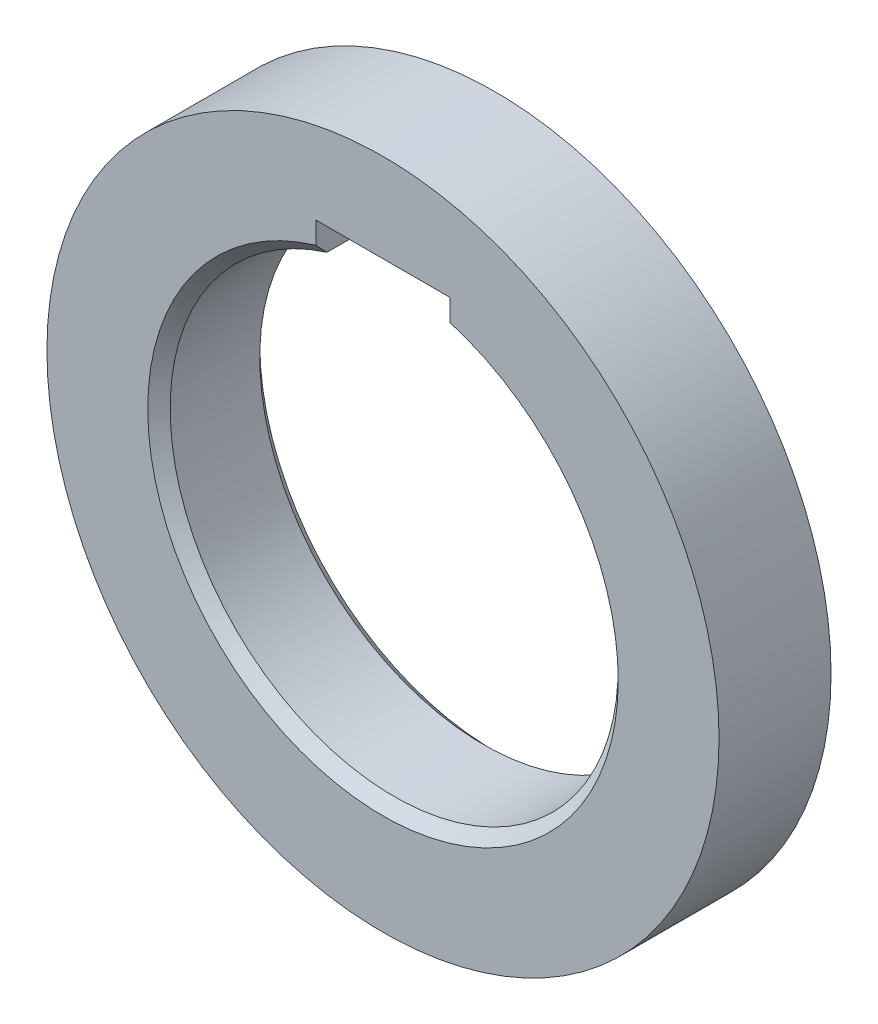
SolidWorks part; units mm, degrees
material "1023 Carbon Steel Sheet (SS)"
ref_plane "Front Plane" through (0, 0, 0) normal (0, 0, 1) x (1, 0, 0)
ref_plane "Top Plane" through (0, 0, 0) normal (0, 1, 0) x (1, 0, 0)
ref_plane "Right Plane" through (0, 0, 0) normal (1, 0, 0) x (0, 0, -1)
sketch "Sketch1" plane through (0, 0, 0) normal (0, 0, 1) x (1, 0, 0)
  line L0 (0, 0) -> (0, 22.0788) construction
  line L1 (6, 19.0788) -> (6, 22.0788)
  line L2 (-6, 19.0788) -> (-6, 22.0788)
  line L3 (-6, 19.0788) -> (-6, 22.0788)
  line L4 (-6, 22.0788) -> (6, 22.0788)
  line L5 (6, 0) -> (6, 64.1476) construction
  line L6 (0, 0) -> (0, 64.1476) construction
  line L7 (-6, 0) -> (-6, 64.1476) construction
  arc A0 (-6, 19.0788) -> (6, 19.0788) centre (0, 0) ccw
  circle A1 centre (0, 0) radius 30
  dimension "D1" = 40
  dimension "D5" = 60
  dimension "D4" = 3
  dimension "D2" = 6
  dimension "D3" = 6
extrude "Boss-Extrude1" add sketch "Sketch1" against normal blind 10 contours A1 A0 L2 L4 L1
chamfer "Chamfer1" distance 1 angle 45 2 edges at (0, -20, -10) (0, -20, 0)
